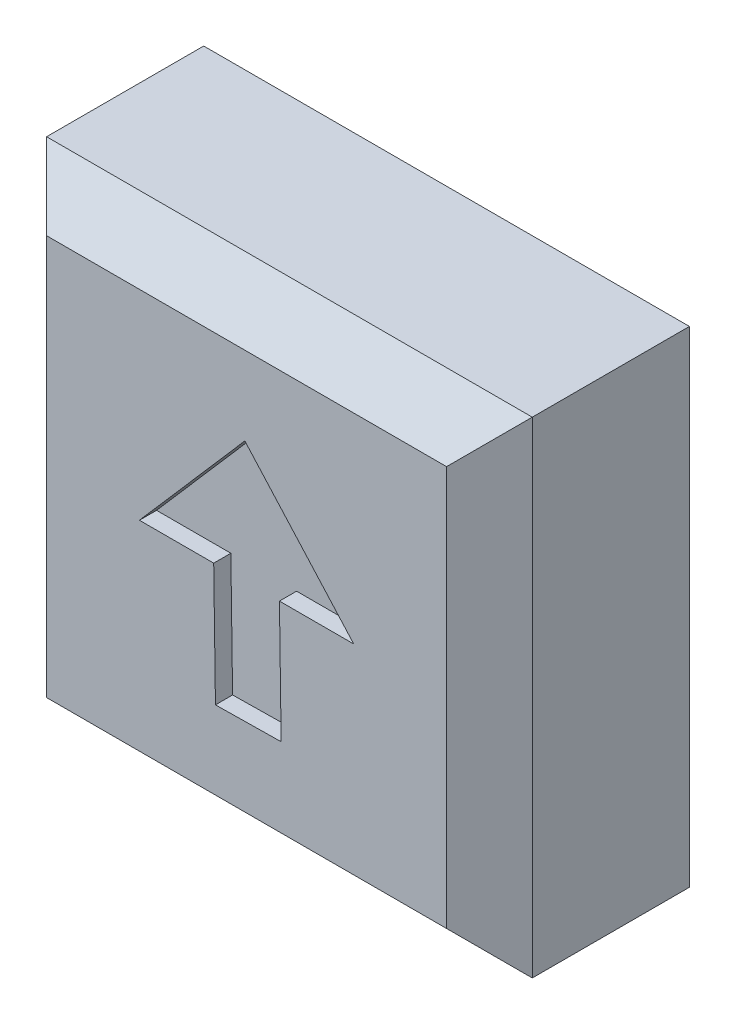
SolidWorks part; units mm, degrees
ref_plane "Front Plane" through (0, 0, 0) normal (1, 0, 0) x (0, 1, 0)
ref_plane "Top Plane" through (0, 0, 0) normal (0, 0, 1) x (0, 1, 0)
ref_plane "Right Plane" through (0, 0, 0) normal (0, 1, 0) x (-1, 0, 0)
sketch "Sketch1" plane through (0, 0, 0) normal (0, 0, 1) x (0, 1, 0)
  line L1 (-2.1, -0.625) -> (2.1, -0.625)
  line L2 (-2.1, -0.625) -> (-2.1, 0.625)
  line L3 (-2.1, 0.625) -> (2.1, 0.625)
  line L4 (2.1, -0.625) -> (2.1, 0.625)
  line L5 (-2.1, -0.625) -> (2.1, 0.625) construction
  line L6 (-2.1, 0.625) -> (2.1, -0.625) construction
  line L7 (-0.7, -2.1) -> (0.7, -2.1)
  line L8 (-0.7, -2.1) -> (-0.7, 2.1)
  line L9 (-0.7, 2.1) -> (0.7, 2.1)
  line L10 (0.7, -2.1) -> (0.7, 2.1)
  line L11 (-0.7, -2.1) -> (0.7, 2.1) construction
  line L12 (-0.7, 2.1) -> (0.7, -2.1) construction
  circle A0 centre (0, 0) radius 2.75
  dimension "D1" = 5.5
  dimension "D2" = 1.25
  dimension "D3" = 1.4
  dimension "D4" = 4.2
  dimension "D5" = 4.2
extrude "Boss-Extrude1" add sketch "Sketch1" along normal blind 4 contours A0 L10 L7 L8 L1 L2 L3 L9 L4
sketch "Sketch2" plane through (0, 0, 4) normal (0, 0, 1) x (1, 0, 0)
  line L1 (-8.5, -8.5) -> (8.5, -8.5)
  line L2 (-8.5, -8.5) -> (-8.5, 8.5)
  line L3 (-8.5, 8.5) -> (8.5, 8.5)
  line L4 (8.5, -8.5) -> (8.5, 8.5)
  line L5 (-8.5, -8.5) -> (8.5, 8.5) construction
  line L6 (-8.5, 8.5) -> (8.5, -8.5) construction
  point P0 (0, 0)
  dimension "D1" = 17
  dimension "D2" = 17
extrude "Boss-Extrude2" add sketch "Sketch2" along normal blind 1
sketch "Sketch3" plane through (0, 0, 4) normal (0, 0, -1) x (1, 0, 0)
  line L0 (-7.5, 7.5) -> (-7.5, -7.5)
  line L1 (-8.5, 8.5) -> (8.5, 8.5)
  line L2 (-8.5, 8.5) -> (-8.5, -8.5)
  line L3 (-8.5, -8.5) -> (8.5, -8.5)
  line L4 (8.5, 8.5) -> (8.5, -8.5)
  line L5 (-7.5, -7.5) -> (7.5, -7.5)
  line L6 (7.5, 7.5) -> (7.5, -7.5)
  line L7 (-7.5, 7.5) -> (7.5, 7.5)
  point P4 (0, 0)
  line M10 (8.5, -8.5) -> (8.5, 8.5)
  line M11 (8.5, 8.5) -> (-8.5, 8.5)
  line M12 (-8.5, 8.5) -> (-8.5, -8.5)
  line M13 (-8.5, -8.5) -> (8.5, -8.5)
  dimension "D1" = 1
extrude "Boss-Extrude3" add sketch "Sketch3" along normal blind 6 contours L0 L7 L6 L5 M13 M10 M11 M12
chamfer "Chamfer1" distance 1.5 angle 45 9 edges at (0, -8.5, 5) (-8.5, 0, 5) (0, 8.5, 5) (8.5, 0, 5) (2.75, 0, 4) (0, -7.5, 4) (7.5, 0, 4) (0, 7.5, 4) (-7.5, 0, 4)
chamfer "Chamfer2" distance 4 distance2 0.5 4 edges at (7.5, 0, -2) (0, 7.5, -2) (-7.5, 0, -2) (0, -7.5, -2)
sketch "Sketch4" plane through (0, 0, 5) normal (0, 0, 1) x (1, 0, 0)
  line L0 (-1.2105, 4.2332) -> (-1.0895, -4.2659)
  line L1 (-7, -7) -> (7, -7) construction
  line L2 (-7, -7) -> (-7, 7) construction
  line L3 (-7, 7) -> (7, 7) construction
  line L4 (7, -7) -> (7, 7) construction
  line L5 (0, -7) -> (-7, -7) construction
  line L6 (0, -7) -> (0, 0) construction
  line L7 (0, 0) -> (-7, 0) construction
  line L8 (-7, -7) -> (-7, 0) construction
  line L9 (-1.2105, 4.2332) -> (1.0895, 4.2659)
  line L10 (-1.0895, -4.2659) -> (1.2105, -4.2332)
  line L11 (1.0895, 4.2659) -> (1.2105, -4.2332)
  line L12 (-1.2105, 4.2332) -> (1.2105, -4.2332) construction
  line L13 (-1.0895, -4.2659) -> (1.0895, 4.2659) construction
  line L14 (3.75, -1.15) -> (-3.75, -1.15)
  line L15 (3.75, -1.15) -> (3.75, 1.15)
  line L16 (-3.75, -1.15) -> (-3.75, 1.15)
  line L17 (3.75, 1.15) -> (-3.75, 1.15)
  line L18 (3.75, -1.15) -> (-3.75, 1.15) construction
  line L19 (-3.75, -1.15) -> (3.75, 1.15) construction
  line L20 (-0.0605, 4.2496) -> (-3.75, 0)
  line L21 (-0.0605, 4.2496) -> (3.75, 0)
  line L22 (3.75, 0) -> (-3.75, 0)
  dimension "D1" = 7.5
  dimension "D2" = 8.5
  dimension "D3" = 2.3
  dimension "D4" = 2.3
extrude "Cut-Extrude1" cut sketch "Sketch4" against normal blind 0.6 contours L21 L20 L0 L17 L11 | L0 L20 L17 | L22 L0 L17 L20 | L22 L11 L17 L0 | L21 L11 L17 | L22 L21 L17 L11 | L11 L14 L0 L10 | L11 L22 L0 L14
fillet "Fillet1" [suppressed] radius 0.25
fillet "Fillet2" [suppressed] radius 1
sketch "Sketch5" plane through (0, 0, 4) normal (0, 0, -1) x (1, 0, 0)
  line L0 (-7.5, -7.5) -> (7.5, -7.5) construction
  line L1 (-7.5, 7.5) -> (7.4895, 7.5)
  line L2 (-7.5, 7.5) -> (-7.5, -7.5)
  line L3 (-7.5, -7.5) -> (7.4895, -7.5)
  line L4 (7.4895, 7.5) -> (7.4895, -7.5)
  line L5 (-7.5, 7.5) -> (7.4895, -7.5) construction
  line L6 (-7.5, -7.5) -> (7.4895, 7.5) construction
  circle A0 centre (0, 0) radius 2.75
  point P4 (-0.0052, 0)
extrude "Boss-Extrude4" add sketch "Sketch5" along normal blind 0.5
equation "\"D4@Sketch4\"=\"D3@Sketch4\""
